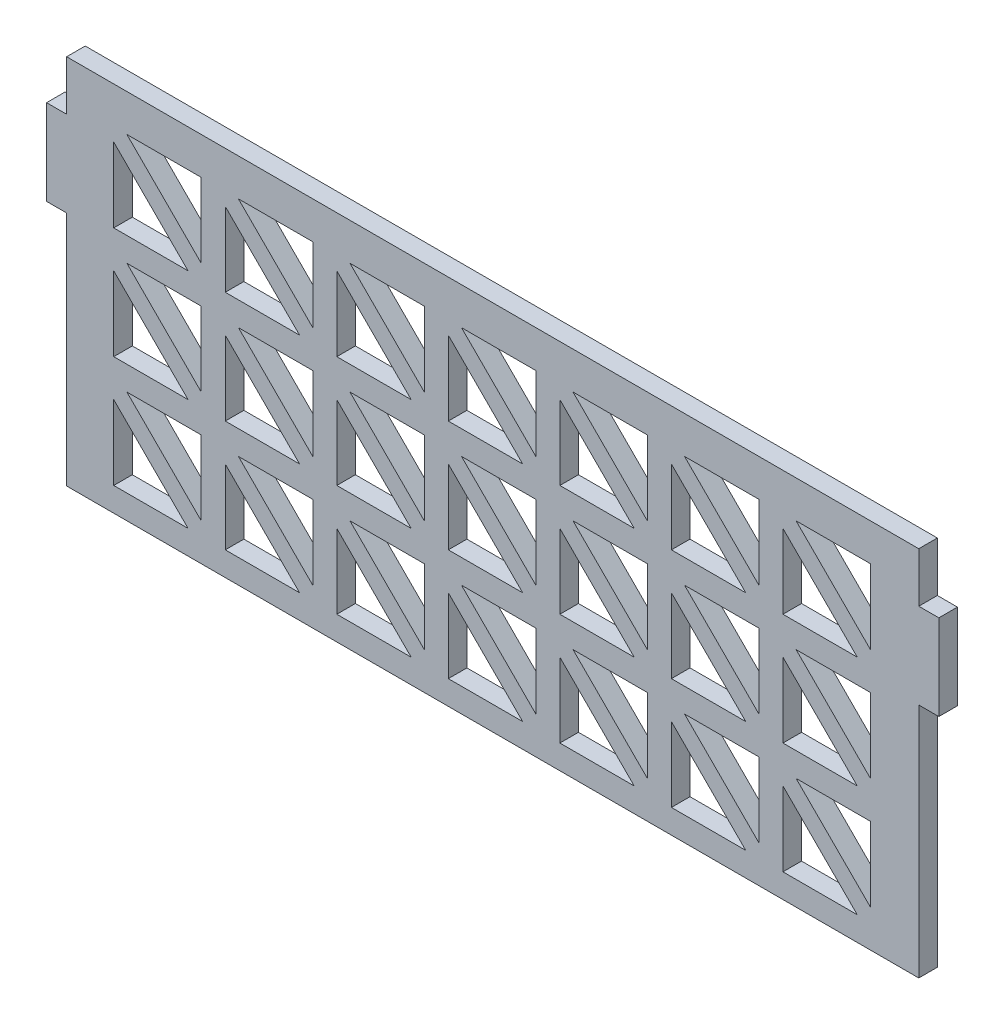
SolidWorks part; units mm, degrees
ref_plane "Front Plane" through (0, 0, 0) normal (0, 0, 1) x (1, 0, 0)
ref_plane "Top Plane" through (0, 0, 0) normal (0, 1, 0) x (1, 0, 0)
ref_plane "Right Plane" through (0, 0, 0) normal (1, 0, 0) x (0, 0, -1)
sketch "Sketch1" plane through (0, 0, 0) normal (0, 0, 1) x (1, 0, 0)
  line L1 (0, 0) -> (152.4, 0)
  line L2 (0, 0) -> (0, 241.3)
  line L3 (0, 241.3) -> (152.4, 241.3)
  line L4 (152.4, 0) -> (152.4, 241.3)
  dimension "D1" = 241.3
  dimension "D2" = 152.4
extrude "Boss-Extrude1" add sketch "Sketch1" along normal blind 3.175
sketch "Sketch2" plane through (0, 0, 3.175) normal (0, 0, 1) x (1, 0, 0)
  line L0 (152.4, 0) -> (152.4, 241.3) construction
  line L1 (152.4, 223.139) -> (148.971, 223.139)
  line L2 (152.4, 223.139) -> (152.4, 54.991)
  line L3 (152.4, 54.991) -> (148.971, 54.991)
  line L4 (148.971, 223.139) -> (148.971, 54.991)
  line L5 (0, 241.3) -> (0, 0) construction
  line L6 (0, 223.139) -> (3.429, 223.139)
  line L7 (0, 223.139) -> (0, 54.991)
  line L8 (0, 54.991) -> (3.429, 54.991)
  line L9 (3.429, 223.139) -> (3.429, 54.991)
  line L10 (152.4, 241.3) -> (0, 241.3) construction
  line L12 (152.4, 0) -> (148.971, 0)
  line L13 (152.4, 0) -> (152.4, 40.386)
  line L14 (152.4, 40.386) -> (148.971, 40.386)
  line L15 (148.971, 0) -> (148.971, 40.386)
  line L16 (0, 0) -> (3.429, 0)
  line L17 (0, 0) -> (0, 40.386)
  line L18 (0, 40.386) -> (3.429, 40.386)
  line L19 (3.429, 0) -> (3.429, 40.386)
  dimension "D1" = 18.161
  dimension "D2" = 14.605
  dimension "D3" = 3.429
  dimension "D4" = 40.386
extrude "Cut-Extrude1" cut sketch "Sketch2" against normal through all
sketch "Sketch3" plane through (0, 0, 3.175) normal (0, 0, 1) x (1, 0, 0)
  line L0 (3.429, 57.15) -> (148.971, 57.15) construction
  line L1 (3.429, 0) -> (148.971, 0) construction
  line L2 (148.971, 223.139) -> (148.971, 54.991) construction
  line L3 (3.429, 54.991) -> (3.429, 223.139) construction
  line L4 (128.016, 57.15) -> (140.716, 57.15)
  line L5 (140.716, 57.15) -> (140.716, 44.45)
  line L6 (140.716, 44.45) -> (128.016, 57.15)
  line L7 (125.7709, 57.15) -> (140.716, 42.2049) construction
  line L8 (125.7709, 42.2049) -> (138.4709, 42.2049)
  line L9 (125.7709, 54.9049) -> (125.7709, 42.2049)
  line L10 (138.4709, 42.2049) -> (125.7709, 54.9049)
  line L11 (108.966, 57.15) -> (121.666, 57.15)
  line L12 (121.666, 44.45) -> (108.966, 57.15)
  line L13 (119.4209, 42.2049) -> (106.7209, 54.9049)
  line L14 (106.7209, 54.9049) -> (106.7209, 42.2049)
  line L15 (106.7209, 42.2049) -> (119.4209, 42.2049)
  line L16 (121.666, 57.15) -> (121.666, 44.45)
  line L17 (89.916, 57.15) -> (102.616, 57.15)
  line L18 (102.616, 44.45) -> (89.916, 57.15)
  line L19 (100.3709, 42.2049) -> (87.6709, 54.9049)
  line L20 (87.6709, 54.9049) -> (87.6709, 42.2049)
  line L21 (87.6709, 42.2049) -> (100.3709, 42.2049)
  line L22 (102.616, 57.15) -> (102.616, 44.45)
  line L23 (70.866, 57.15) -> (83.566, 57.15)
  line L24 (83.566, 44.45) -> (70.866, 57.15)
  line L25 (81.3209, 42.2049) -> (68.6209, 54.9049)
  line L26 (68.6209, 54.9049) -> (68.6209, 42.2049)
  line L27 (68.6209, 42.2049) -> (81.3209, 42.2049)
  line L28 (83.566, 57.15) -> (83.566, 44.45)
  line L29 (51.816, 57.15) -> (64.516, 57.15)
  line L30 (64.516, 44.45) -> (51.816, 57.15)
  line L31 (62.2709, 42.2049) -> (49.5709, 54.9049)
  line L32 (49.5709, 54.9049) -> (49.5709, 42.2049)
  line L33 (49.5709, 42.2049) -> (62.2709, 42.2049)
  line L34 (64.516, 57.15) -> (64.516, 44.45)
  line L35 (32.766, 57.15) -> (45.466, 57.15)
  line L36 (45.466, 44.45) -> (32.766, 57.15)
  line L37 (43.2209, 42.2049) -> (30.5209, 54.9049)
  line L38 (30.5209, 54.9049) -> (30.5209, 42.2049)
  line L39 (30.5209, 42.2049) -> (43.2209, 42.2049)
  line L40 (45.466, 57.15) -> (45.466, 44.45)
  line L41 (13.716, 57.15) -> (26.416, 57.15)
  line L42 (26.416, 44.45) -> (13.716, 57.15)
  line L43 (24.1709, 42.2049) -> (11.4709, 54.9049)
  line L44 (11.4709, 54.9049) -> (11.4709, 42.2049)
  line L45 (11.4709, 42.2049) -> (24.1709, 42.2049)
  line L46 (26.416, 57.15) -> (26.416, 44.45)
  line L47 (128.016, 38.1) -> (140.716, 38.1)
  line L48 (16.764, 188.849) -> (136.144, 188.849)
  line L49 (16.764, 188.849) -> (16.764, 69.469)
  line L50 (16.764, 69.469) -> (136.144, 69.469)
  line L51 (136.144, 188.849) -> (136.144, 69.469)
  line L52 (140.716, 38.1) -> (140.716, 25.4)
  line L53 (140.716, 25.4) -> (128.016, 38.1)
  line L54 (125.7709, 23.1549) -> (138.4709, 23.1549)
  line L55 (125.7709, 35.8549) -> (125.7709, 23.1549)
  line L56 (138.4709, 23.1549) -> (125.7709, 35.8549)
  line L57 (108.966, 38.1) -> (121.666, 38.1)
  line L58 (121.666, 25.4) -> (108.966, 38.1)
  line L59 (119.4209, 23.1549) -> (106.7209, 35.8549)
  line L60 (106.7209, 35.8549) -> (106.7209, 23.1549)
  line L61 (106.7209, 23.1549) -> (119.4209, 23.1549)
  line L62 (121.666, 38.1) -> (121.666, 25.4)
  line L63 (89.916, 38.1) -> (102.616, 38.1)
  line L64 (102.616, 25.4) -> (89.916, 38.1)
  line L65 (100.3709, 23.1549) -> (87.6709, 35.8549)
  line L66 (87.6709, 35.8549) -> (87.6709, 23.1549)
  line L67 (87.6709, 23.1549) -> (100.3709, 23.1549)
  line L68 (102.616, 38.1) -> (102.616, 25.4)
  line L69 (70.866, 38.1) -> (83.566, 38.1)
  line L70 (83.566, 25.4) -> (70.866, 38.1)
  line L71 (81.3209, 23.1549) -> (68.6209, 35.8549)
  line L72 (68.6209, 35.8549) -> (68.6209, 23.1549)
  line L73 (68.6209, 23.1549) -> (81.3209, 23.1549)
  line L74 (83.566, 38.1) -> (83.566, 25.4)
  line L75 (51.816, 38.1) -> (64.516, 38.1)
  line L76 (64.516, 25.4) -> (51.816, 38.1)
  line L77 (62.2709, 23.1549) -> (49.5709, 35.8549)
  line L78 (49.5709, 35.8549) -> (49.5709, 23.1549)
  line L79 (49.5709, 23.1549) -> (62.2709, 23.1549)
  line L80 (64.516, 38.1) -> (64.516, 25.4)
  line L81 (32.766, 38.1) -> (45.466, 38.1)
  line L82 (45.466, 25.4) -> (32.766, 38.1)
  line L83 (43.2209, 23.1549) -> (30.5209, 35.8549)
  line L84 (30.5209, 35.8549) -> (30.5209, 23.1549)
  line L85 (30.5209, 23.1549) -> (43.2209, 23.1549)
  line L86 (45.466, 38.1) -> (45.466, 25.4)
  line L87 (13.716, 38.1) -> (26.416, 38.1)
  line L88 (26.416, 25.4) -> (13.716, 38.1)
  line L89 (24.1709, 23.1549) -> (11.4709, 35.8549)
  line L90 (11.4709, 35.8549) -> (11.4709, 23.1549)
  line L91 (11.4709, 23.1549) -> (24.1709, 23.1549)
  line L92 (26.416, 38.1) -> (26.416, 25.4)
  line L93 (128.016, 19.05) -> (140.716, 19.05)
  line L94 (140.716, 19.05) -> (140.716, 6.35)
  line L95 (140.716, 6.35) -> (128.016, 19.05)
  line L96 (125.7709, 4.1049) -> (138.4709, 4.1049)
  line L97 (125.7709, 16.8049) -> (125.7709, 4.1049)
  line L98 (138.4709, 4.1049) -> (125.7709, 16.8049)
  line L99 (108.966, 19.05) -> (121.666, 19.05)
  line L100 (121.666, 6.35) -> (108.966, 19.05)
  line L101 (119.4209, 4.1049) -> (106.7209, 16.8049)
  line L102 (106.7209, 16.8049) -> (106.7209, 4.1049)
  line L103 (106.7209, 4.1049) -> (119.4209, 4.1049)
  line L104 (121.666, 19.05) -> (121.666, 6.35)
  line L105 (89.916, 19.05) -> (102.616, 19.05)
  line L106 (102.616, 6.35) -> (89.916, 19.05)
  line L107 (100.3709, 4.1049) -> (87.6709, 16.8049)
  line L108 (87.6709, 16.8049) -> (87.6709, 4.1049)
  line L109 (87.6709, 4.1049) -> (100.3709, 4.1049)
  line L110 (102.616, 19.05) -> (102.616, 6.35)
  line L111 (70.866, 19.05) -> (83.566, 19.05)
  line L112 (83.566, 6.35) -> (70.866, 19.05)
  line L113 (81.3209, 4.1049) -> (68.6209, 16.8049)
  line L114 (68.6209, 16.8049) -> (68.6209, 4.1049)
  line L115 (68.6209, 4.1049) -> (81.3209, 4.1049)
  line L116 (83.566, 19.05) -> (83.566, 6.35)
  line L117 (51.816, 19.05) -> (64.516, 19.05)
  line L118 (64.516, 6.35) -> (51.816, 19.05)
  line L119 (62.2709, 4.1049) -> (49.5709, 16.8049)
  line L120 (49.5709, 16.8049) -> (49.5709, 4.1049)
  line L121 (49.5709, 4.1049) -> (62.2709, 4.1049)
  line L122 (64.516, 19.05) -> (64.516, 6.35)
  line L123 (32.766, 19.05) -> (45.466, 19.05)
  line L124 (45.466, 6.35) -> (32.766, 19.05)
  line L125 (43.2209, 4.1049) -> (30.5209, 16.8049)
  line L126 (30.5209, 16.8049) -> (30.5209, 4.1049)
  line L127 (30.5209, 4.1049) -> (43.2209, 4.1049)
  line L128 (45.466, 19.05) -> (45.466, 6.35)
  line L129 (13.716, 19.05) -> (26.416, 19.05)
  line L130 (26.416, 6.35) -> (13.716, 19.05)
  line L131 (24.1709, 4.1049) -> (11.4709, 16.8049)
  line L132 (11.4709, 16.8049) -> (11.4709, 4.1049)
  line L133 (11.4709, 4.1049) -> (24.1709, 4.1049)
  line L134 (26.416, 19.05) -> (26.416, 6.35)
  line L136 (16.764, 228.219) -> (91.3765, 228.219)
  line L137 (16.764, 228.219) -> (16.764, 202.819)
  line L138 (16.764, 202.819) -> (91.3765, 202.819)
  line L139 (91.3765, 228.219) -> (91.3765, 202.819)
  line L148 (123.444, 219.075) -> (136.144, 219.075)
  line L149 (123.444, 219.075) -> (123.444, 202.819)
  line L150 (123.444, 202.819) -> (136.144, 202.819)
  line L151 (136.144, 219.075) -> (136.144, 202.819)
  line L156 (101.4095, 210.058) -> (106.7435, 210.058)
  line L157 (101.4095, 210.058) -> (101.4095, 202.819)
  line L158 (101.4095, 202.819) -> (106.7435, 202.819)
  line L159 (106.7435, 210.058) -> (106.7435, 202.819)
  point P152 (104.0765, 210.058)
  dimension "D1" = 57.15
  dimension "D2" = 12.7
  dimension "D3" = 8.255
  dimension "D4" = 1.5875
  dimension "D6" = 188.849
  dimension "D7" = 119.38
  dimension "D8" = 13.335
  dimension "D10" = 74.6125
  dimension "D11" = 25.4
  dimension "D12" = 16.256
  dimension "D13" = 12.7
  dimension "D15" = 5.334
  dimension "D16" = 7.239
  dimension "D17" = 13.97
  dimension "D18" = 12.7
  dimension "D5" = 7
  dimension "D9" = 3
extrude "Cut-Extrude2" cut sketch "Sketch3" against normal through all
sketch "Sketch4" plane through (0, 0, 3.175) normal (0, 0, 1) x (1, 0, 0)
  line L0 (3.429, 63.5) -> (148.971, 63.5) construction
  line L1 (3.429, 54.991) -> (3.429, 223.139) construction
  line L2 (148.971, 223.139) -> (148.971, 54.991) construction
  line L3 (3.429, 0) -> (148.971, 0) construction
  line L5 (173.1699, 63.5) -> (-21.1143, 63.5)
  line L6 (173.1699, 63.5) -> (173.1699, 243.7659)
  line L7 (173.1699, 243.7659) -> (-21.1143, 243.7659)
  line L8 (-21.1143, 63.5) -> (-21.1143, 243.7659)
  dimension "D1" = 63.5
extrude "Cut-Extrude4" cut sketch "Sketch4" against normal through all
